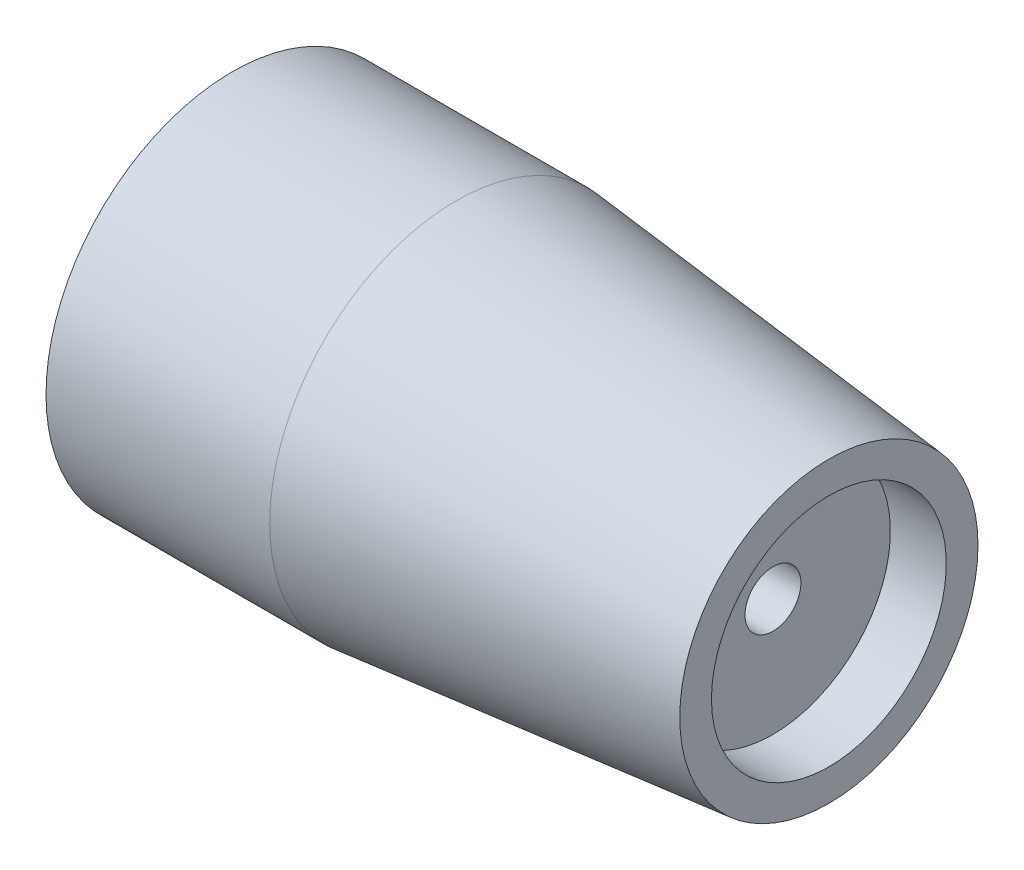
SolidWorks part; units mm, degrees
ref_plane "Ebene vorne" through (0, 0, 0) normal (0, 0, 1) x (1, 0, 0)
ref_plane "Ebene oben" through (0, 0, 0) normal (0, 1, 0) x (1, 0, 0)
ref_plane "Ebene rechts" through (0, 0, 0) normal (1, 0, 0) x (0, 0, -1)
sketch "Skizze1" plane through (0, 0, 0) normal (0, 0, 1) x (1, 0, 0)
  line L0 (0, 0) -> (7.5, 0) construction
  line L1 (7.5, 0) -> (7.5, 3.15)
  line L2 (7.5, 3.15) -> (9, 3.15)
  line L3 (9, 3.15) -> (9, 4)
  line L4 (9, 4) -> (-1, 5)
  line L5 (-1, 5) -> (-7, 5)
  line L6 (-7, 5) -> (-7, 2.3)
  line L7 (-7, 2.3) -> (0, 2.3)
  line L8 (0, 2.3) -> (0, 0)
  line L9 (0, 0) -> (7.5, 0)
  point P6 (-7.7115, 7.5)
  dimension "D1" = 16
  dimension "D2" = 4.6
  dimension "D3" = 10
  dimension "D4" = 1.5
  dimension "D5" = 6.3
  dimension "D6" = 8
  dimension "D7" = 6
  dimension "D8" = 7
revolve "Rotation1" add sketch "Skizze1" angle 360 about L0
sketch "Skizze2" plane through (7.5, 0, 0) normal (1, 0, 0) x (0, 0, -1)
  circle A0 centre (0, 0) radius 0.75
  dimension "D1" = 1.5
extrude "Schnitt-Linear austragen1" cut sketch "Skizze2" against normal through all
sketch "Skizze3" plane through (0, 0, 0) normal (-1, 0, 0) x (0, 0, 1)
  circle A0 centre (0, 0) radius 0.75 construction
  circle A1 centre (0, 0) radius 0.75
extrude "Aufsatz-Linear austragen1" add sketch "Skizze3" against normal blind 0.2
